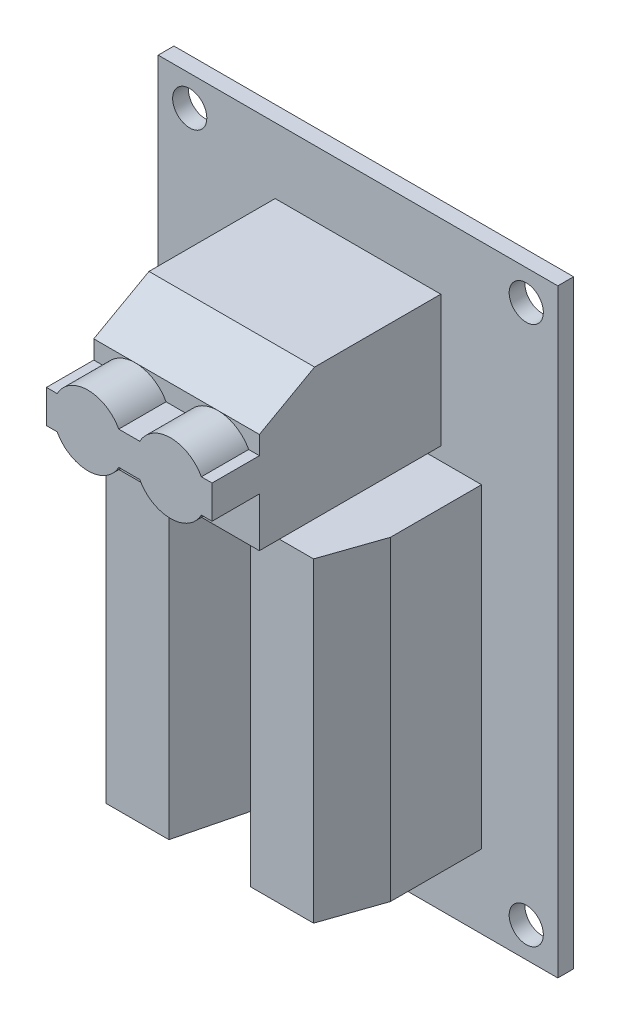
SolidWorks part; units mm, degrees
ref_plane "Front Plane" through (0, 0, 0) normal (1, 0, 0) x (0, 1, 0)
ref_plane "Top Plane" through (0, 0, 0) normal (0, 0, 1) x (0, 1, 0)
ref_plane "Right Plane" through (0, 0, 0) normal (0, 1, 0) x (-1, 0, 0)
sketch "Sketch1" plane through (0, 0, 0) normal (0, 0, 1) x (0, 1, 0)
  line L1 (28.5, -19) -> (-28.5, -19)
  line L2 (28.5, -19) -> (28.5, 19)
  line L3 (28.5, 19) -> (-28.5, 19)
  line L4 (-28.5, -19) -> (-28.5, 19)
  line L5 (0, 19) -> (0, -19) construction
  line L6 (28.5, 0) -> (-28.5, 0) construction
  point P0 (0, 0)
  dimension "D1" = 57
  dimension "D2" = 38
extrude "Boss-Extrude1" add sketch "Sketch1" along normal blind 1.5
sketch "Sketch2" plane through (0, 0, 1.5) normal (0, 0, 1) x (1, 0, 0)
  line L0 (0, 0) -> (-50000, 0) construction
  line L1 (0, 0) -> (0, -50000) construction
  line L2 (19, 28.5) -> (-19, 28.5) construction
  line L3 (-19, 28.5) -> (-19, -28.5) construction
  circle A0 centre (-16, 25.625) radius 1.625
  circle A1 centre (-16, -25.625) radius 1.625
  circle A2 centre (16, 25.625) radius 1.625
  circle A3 centre (16, -25.625) radius 1.625
  point P13 (-16, 27.25)
  point P16 (-17.625, 25.625)
  dimension "D1" = 3.25
  dimension "D2" = 51.25
  dimension "D3" = 32
  dimension "D4" = 1.25
  dimension "D5" = 1.375
extrude "Cut-Extrude1" cut sketch "Sketch2" against normal through all
sketch "Sketch3" plane through (0, 0, 1.5) normal (0, 0, 1) x (1, 0, 0)
  line L0 (-19, -28.5) -> (19, -28.5) construction
  line L1 (11.75, -21.5) -> (-11.75, -21.5)
  line L2 (11.75, -21.5) -> (11.75, 8.5)
  line L3 (11.75, 8.5) -> (-11.75, 8.5)
  line L4 (-11.75, -21.5) -> (-11.75, 8.5)
  line L5 (0, 8.5) -> (0, -21.5) construction
  line L6 (11.75, -6.5) -> (-11.75, -6.5) construction
  line L7 (19, -28.5) -> (19, 28.5) construction
  line L8 (-19, 28.5) -> (-19, -28.5) construction
  point P0 (0, -6.5)
  point P4 (0, -8.7722)
  dimension "D1" = 30
  dimension "D2" = 23.5
  dimension "D3" = 7
  dimension "D4" = 7.25
  dimension "D5" = 7.25
extrude "Boss-Extrude2" add sketch "Sketch3" along normal blind 14.1
sketch "Sketch4" plane through (0, 0, 15.6) normal (0, 0, 1) x (1, 0, 0)
  line L0 (11.75, 8.5) -> (-11.75, 8.5) construction
  line L1 (1.625, -21.5) -> (-1.625, -21.5)
  line L2 (1.625, -21.5) -> (1.625, 8.5)
  line L3 (1.625, 8.5) -> (-1.625, 8.5)
  line L4 (-1.625, -21.5) -> (-1.625, 8.5)
  line L5 (0, 8.5) -> (0, -21.5) construction
  line L6 (1.625, -6.5) -> (-1.625, -6.5) construction
  line L7 (-11.75, -21.5) -> (11.75, -21.5) construction
  point P0 (0, -6.5)
  point P6 (2.15, -21.5)
  dimension "D1" = 3.25
extrude "Cut-Extrude2" cut sketch "Sketch4" against normal up to surface (14.1 mm away) up to face at (0, -6.5, 1.5)
sketch "Sketch5" plane through (0, -21.5, 0) normal (0, -1, 0) x (1, 0, 0)
  line L0 (-11.75, 10.1643) -> (-9.875, 15.6)
  line L1 (-11.75, 15.6) -> (-11.75, 1.5) construction
  line L2 (-11.75, 15.6) -> (-1.625, 15.6) construction
  line L3 (-9.875, 15.6) -> (-11.75, 15.6)
  line L4 (-11.75, 15.6) -> (-11.75, 10.1643)
  line L5 (-1.625, 15.6) -> (-3.875, 15.6)
  line L6 (-3.875, 15.6) -> (-1.625, 6.6)
  line L7 (-1.625, 1.5) -> (-1.625, 15.6) construction
  line L8 (-1.625, 6.6) -> (-1.625, 15.6)
  line L9 (0, 0) -> (0, -2.2929) construction
  line L10 (1.625, 6.6) -> (1.625, 15.6)
  line L12 (3.875, 15.6) -> (1.625, 6.6)
  line L13 (1.625, 15.6) -> (3.875, 15.6)
  line L14 (11.75, 15.6) -> (11.75, 10.1643)
  line L15 (9.875, 15.6) -> (11.75, 15.6)
  line L16 (11.75, 10.1643) -> (9.875, 15.6)
  point P15 (-11.75, 10.1038)
  point P20 (-10.1013, 8.5615)
  point P23 (-8.0709, 2.7203)
  dimension "D1" = 9
  dimension "D2" = 6
  dimension "D3" = 5.75
  dimension "D4" = 7.75
extrude "Cut-Extrude3" cut sketch "Sketch5" against normal through all
sketch "Sketch6" plane through (0, 0, 1.5) normal (0, 0, 1) x (1, 0, 0)
  line L0 (19, 28.5) -> (-19, 28.5) construction
  line L1 (7.875, 22.25) -> (-7.875, 22.25)
  line L2 (7.875, 22.25) -> (7.875, 9.75)
  line L3 (7.875, 9.75) -> (-7.875, 9.75)
  line L4 (-7.875, 22.25) -> (-7.875, 9.75)
  line L5 (0, 9.75) -> (0, 22.25) construction
  line L6 (7.875, 16) -> (-7.875, 16) construction
  point P0 (0, 16)
  dimension "D1" = 15.75
  dimension "D2" = 12.5
  dimension "D3" = 6.25
extrude "Boss-Extrude3" add sketch "Sketch6" along normal blind 21.75 separate body
sketch "Sketch8" plane through (0, 0, 23.25) normal (0, 0, 1) x (1, 0, 0)
  line L0 (-7.875, 16) -> (7.875, 16) construction
  line L1 (-7.875, 22.25) -> (-7.875, 9.75) construction
  line L2 (7.875, 9.75) -> (7.875, 22.25) construction
  line L3 (0, 22.25) -> (0, 9.75) construction
  line L4 (7.875, 22.25) -> (-7.875, 22.25) construction
  line L5 (-7.875, 9.75) -> (7.875, 9.75) construction
  line L6 (-1, 17.575) -> (1, 17.575)
  line L7 (-1, 14.425) -> (1, 14.425)
  line L8 (-6.8566, 17.575) -> (-7.875, 17.575)
  line L9 (-7.875, 17.575) -> (-7.875, 14.425)
  line L10 (-7.875, 14.425) -> (-6.8566, 14.425)
  line L11 (7.875, 14.425) -> (6.8566, 14.425)
  line L12 (7.875, 17.575) -> (7.875, 14.425)
  line L13 (6.8566, 17.575) -> (7.875, 17.575)
  circle A0 centre (-3.9283, 16) radius 3.325 construction
  circle A1 centre (3.9283, 16) radius 3.325 construction
  arc A2 (-6.8566, 17.575) -> (-1, 17.575) centre (-3.9283, 16) cw
  arc A3 (-6.8566, 14.425) -> (-1, 14.425) centre (-3.9283, 16) ccw
  arc A4 (6.8566, 14.425) -> (1, 14.425) centre (3.9283, 16) cw
  arc A5 (6.8566, 17.575) -> (1, 17.575) centre (3.9283, 16) ccw
  point P28 (-7.3002, 17.575)
  point P29 (1.0202, 17.575)
  dimension "D1" = 6.65
  dimension "D2" = 3.15
  dimension "D3" = 2
extrude "Cut-Extrude4" cut sketch "Sketch8" against normal blind 4.5 flip side to cut
sketch "Sketch9" plane through (0, 0, 0) normal (1, 0, 0) x (0, 1, 0)
  line L0 (19.325, 18.75) -> (22.25, 13.5)
  line L1 (17.575, 18.75) -> (22.25, 18.75) construction
  line L2 (22.25, 18.75) -> (22.25, 1.5) construction
  line L3 (22.25, 13.5) -> (22.25, 18.75)
  line L4 (22.25, 18.75) -> (19.325, 18.75)
  line L5 (19.325, 18.75) -> (19.325, 23.25) construction
  line L6 (-28.5, 1.5) -> (28.5, 1.5) construction
  point P8 (19.325, 18.75)
  dimension "D1" = 12
extrude "Cut-Extrude5" cut sketch "Sketch9" against normal through all both and the other way through all
